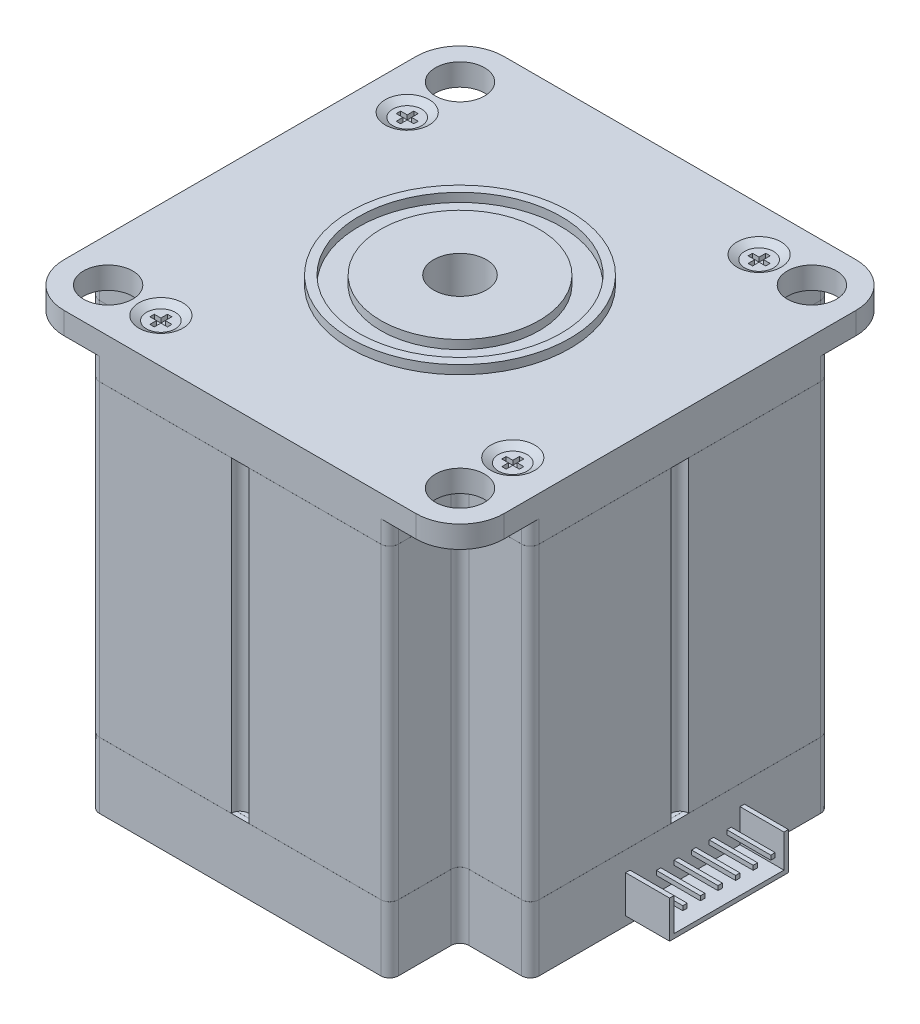
SolidWorks part; units mm, degrees
ref_plane "Front Plane" through (0, 0, 0) normal (0, 0, 1) x (1, 0, 0)
ref_plane "Top Plane" through (0, 0, 0) normal (0, 1, 0) x (1, 0, 0)
ref_plane "Right Plane" through (0, 0, 0) normal (1, 0, 0) x (0, 0, -1)
sketch "Sketch1" plane through (0, 0, 0) normal (0, 1, 0) x (1, 0, 0)
  line L1 (-40, 50) -> (40, 50)
  line L2 (-50, 40) -> (-50, -40)
  line L3 (-40, -50) -> (40, -50)
  line L4 (50, 40) -> (50, -40)
  line L5 (-50, 50) -> (50, -50) construction
  line L6 (-50, -50) -> (50, 50) construction
  arc A0 (40, -50) -> (50, -40) centre (40, -40) ccw
  arc A1 (-40, -50) -> (-50, -40) centre (-40, -40) cw
  arc A2 (40, 50) -> (50, 40) centre (40, 40) cw
  arc A3 (-40, 50) -> (-50, 40) centre (-40, 40) ccw
  circle A4 centre (-40, 40) radius 5.5806
  circle A5 centre (-40, -40) radius 5.5806
  circle A6 centre (40, -40) radius 5.5806
  circle A7 centre (40, 40) radius 5.5806
  point P0 (0, 0)
  dimension "D3" = 10
  dimension "D1" = 100
  dimension "D2" = 100
extrude "Boss-Extrude1" add sketch "Sketch1" along normal mid plane 5
sketch "Sketch2" plane through (0, 2.5, 0) normal (0, 1, 0) x (1, 0, 0)
  line L0 (50, -40) -> (50, 40) construction
  line L1 (-40, -50) -> (40, -50) construction
  line L2 (-50, 40) -> (-50, -40) construction
  line L3 (40, 50) -> (-40, 50) construction
  circle A0 centre (-40, 28) radius 5
  circle A1 centre (28, 40) radius 5
  circle A2 centre (-28, -40) radius 5
  circle A3 centre (40, -28) radius 5
  circle A4 centre (40, 40) radius 5.5806 construction
  circle A5 centre (-40, 40) radius 5.5806 construction
  circle A6 centre (-40, -40) radius 5.5806 construction
  circle A7 centre (40, -40) radius 5.5806 construction
  dimension "D1" = 12
  dimension "D3" = 12
  dimension "D4" = 12
  dimension "D5" = 10
  dimension "D6" = 10
  dimension "D7" = 10
  dimension "D8" = 10
  dimension "D9" = 10
  dimension "D2" = 12
extrude "Cut-Extrude1" cut sketch "Sketch2" against normal blind 1 draft 60
sketch "Sketch3" plane through (0, 1.5, 0) normal (0, 1, 0) x (1, 0, 0)
  line L0 (-39.5, 28.5) -> (-38, 28.5)
  line L1 (-42, 28.5) -> (-40.5, 28.5)
  line L2 (-42, 28.5) -> (-42, 27.5)
  line L3 (-42, 27.5) -> (-40.5, 27.5)
  line L4 (-38, 28.5) -> (-38, 27.5)
  line L5 (27.5, 39.5) -> (27.5, 38)
  line L6 (26, 40.5) -> (27.5, 40.5)
  line L7 (-40.5, 30) -> (-39.5, 30)
  line L8 (-40.5, 30) -> (-40.5, 28.5)
  line L9 (-40.5, 26) -> (-39.5, 26)
  line L10 (-39.5, 30) -> (-39.5, 28.5)
  line L11 (26, 40.5) -> (26, 39.5)
  line L12 (-39.5, 27.5) -> (-39.5, 26)
  line L13 (-40.5, 27.5) -> (-40.5, 26)
  line L14 (-39.5, 27.5) -> (-38, 27.5)
  line L15 (26, 39.5) -> (27.5, 39.5)
  line L16 (30, 40.5) -> (30, 39.5)
  line L17 (-27.5, -40.5) -> (-27.5, -42)
  line L18 (40.5, -27.5) -> (42, -27.5)
  line L19 (27.5, 42) -> (28.5, 42)
  line L20 (27.5, 42) -> (27.5, 40.5)
  line L21 (27.5, 38) -> (28.5, 38)
  line L22 (28.5, 42) -> (28.5, 40.5)
  line L23 (28.5, 39.5) -> (30, 39.5)
  line L24 (28.5, 39.5) -> (28.5, 38)
  line L25 (38, -27.5) -> (39.5, -27.5)
  line L26 (38, -27.5) -> (38, -28.5)
  line L27 (38, -28.5) -> (39.5, -28.5)
  line L28 (42, -27.5) -> (42, -28.5)
  line L31 (39.5, -26) -> (40.5, -26)
  line L32 (39.5, -26) -> (39.5, -27.5)
  line L33 (39.5, -30) -> (40.5, -30)
  line L34 (40.5, -26) -> (40.5, -27.5)
  line L37 (-30, -39.5) -> (-28.5, -39.5)
  line L38 (-30, -39.5) -> (-30, -40.5)
  line L39 (-30, -40.5) -> (-28.5, -40.5)
  line L40 (-26, -39.5) -> (-26, -40.5)
  line L41 (-27.5, -39.5) -> (-26, -39.5)
  line L42 (39.5, -28.5) -> (39.5, -30)
  line L43 (-28.5, -38) -> (-27.5, -38)
  line L44 (-28.5, -38) -> (-28.5, -39.5)
  line L45 (-28.5, -42) -> (-27.5, -42)
  line L46 (-27.5, -38) -> (-27.5, -39.5)
  line L47 (40.5, -28.5) -> (40.5, -30)
  line L48 (-28.5, -40.5) -> (-28.5, -42)
  line L49 (40.5, -28.5) -> (42, -28.5)
  line L50 (28.5, 40.5) -> (30, 40.5)
  line L53 (-27.5, -40.5) -> (-26, -40.5)
  point P0 (-40, 28)
  point P6 (-40, 28)
  point P12 (28, 40)
  point P21 (28, 40)
  point P26 (40, -28)
  point P32 (40, -28)
  point P37 (-28, -40)
  point P43 (-28, -40)
  dimension "D1" = 4
  dimension "D2" = 1
  dimension "D3" = 1
  dimension "D4" = 4
  dimension "D5" = 4
  dimension "D6" = 4
  dimension "D7" = 1
  dimension "D8" = 1
  dimension "D9" = 1
  dimension "D10" = 4
  dimension "D11" = 4
  dimension "D12" = 1
  dimension "D13" = 1
  dimension "D14" = 4
  dimension "D15" = 4
  dimension "D16" = 1
extrude "Cut-Extrude2" cut sketch "Sketch3" against normal blind 1
sketch "Sketch4" plane through (0, -2.5, 0) normal (0, -1, 0) x (1, 0, 0)
  line L0 (-34, 48) -> (-34, 36)
  line L1 (-40, 50) -> (40, 50) construction
  line L2 (-36, 34) -> (-48, 34)
  line L3 (-50, -40) -> (-50, 40) construction
  line L4 (-50, 32) -> (-50, -32)
  line L5 (-48, -34) -> (-36, -34)
  line L6 (-34, -36) -> (-34, -48)
  line L7 (40, -50) -> (-40, -50) construction
  line L8 (-32, -50) -> (32, -50)
  line L9 (34, -48) -> (34, -36)
  line L10 (36, -34) -> (48, -34)
  line L11 (50, 40) -> (50, -40) construction
  line L12 (50, -32) -> (50, 32)
  line L13 (48, 34) -> (36, 34)
  line L14 (34, 36) -> (34, 48)
  line L15 (32, 50) -> (-32, 50)
  arc A0 (32, 50) -> (34, 48) centre (32, 48) cw
  arc A1 (-34, 48) -> (-32, 50) centre (-32, 48) cw
  arc A2 (-32, -50) -> (-34, -48) centre (-32, -48) cw
  arc A3 (32, -50) -> (34, -48) centre (32, -48) ccw
  arc A4 (48, -34) -> (50, -32) centre (48, -32) ccw
  arc A5 (50, 32) -> (48, 34) centre (48, 32) ccw
  arc A6 (-50, 32) -> (-48, 34) centre (-48, 32) cw
  arc A7 (-50, -32) -> (-48, -34) centre (-48, -32) ccw
  arc A8 (-36, -34) -> (-34, -36) centre (-36, -36) cw
  arc A9 (34, -36) -> (36, -34) centre (36, -36) cw
  arc A10 (34, 36) -> (36, 34) centre (36, 36) ccw
  arc A11 (-34, 36) -> (-36, 34) centre (-36, 36) cw
  point P22 (34, 50)
  point P25 (-34, 50)
  point P28 (-34, -50)
  point P31 (34, -50)
  point P34 (50, -34)
  point P37 (50, 34)
  point P40 (-50, 34)
  point P43 (-50, -34)
  point P46 (-34, -34)
  point P49 (34, -34)
  point P52 (34, 34)
  point P55 (-34, 34)
  dimension "D9" = 2
  dimension "D1" = 16
  dimension "D2" = 16
  dimension "D3" = 16
  dimension "D4" = 16
  dimension "D5" = 16
  dimension "D6" = 16
  dimension "D7" = 16
  dimension "D8" = 16
extrude "Boss-Extrude2" add sketch "Sketch4" along normal blind 5
sketch "Sketch9" plane through (0, -7.5, 0) normal (0, -1, 0) x (1, 0, 0)
  line L24 (32, 49) -> (-32, 49)
  line L25 (-33, 48) -> (-33, 36)
  line L26 (-36, 33) -> (-48, 33)
  line L27 (-49, 32) -> (-49, -32)
  line L28 (-48, -33) -> (-36, -33)
  line L29 (-33, -36) -> (-33, -48)
  line L30 (-32, -49) -> (32, -49)
  line L31 (33, -48) -> (33, -36)
  line L32 (36, -33) -> (48, -33)
  line L33 (49, -32) -> (49, 32)
  line L34 (48, 33) -> (36, 33)
  line L35 (33, 36) -> (33, 48)
  line L36 (32, 49) -> (-32, 49)
  line L37 (-33, 48) -> (-33, 36)
  line L38 (-36, 33) -> (-48, 33)
  line L39 (-49, 32) -> (-49, -32)
  line L40 (-48, -33) -> (-36, -33)
  line L41 (-33, -36) -> (-33, -48)
  line L42 (-32, -49) -> (32, -49)
  line L43 (33, -48) -> (33, -36)
  line L44 (36, -33) -> (48, -33)
  line L45 (49, -32) -> (49, 32)
  line L46 (48, 33) -> (36, 33)
  line L47 (33, 36) -> (33, 48)
  arc A24 (33, 48) -> (32, 49) centre (32, 48) ccw
  arc A25 (-32, 49) -> (-33, 48) centre (-32, 48) ccw
  arc A26 (-36, 33) -> (-33, 36) centre (-36, 36) ccw
  arc A27 (-48, 33) -> (-49, 32) centre (-48, 32) ccw
  arc A28 (-49, -32) -> (-48, -33) centre (-48, -32) ccw
  arc A29 (-33, -36) -> (-36, -33) centre (-36, -36) ccw
  arc A30 (-33, -48) -> (-32, -49) centre (-32, -48) ccw
  arc A31 (32, -49) -> (33, -48) centre (32, -48) ccw
  arc A32 (36, -33) -> (33, -36) centre (36, -36) ccw
  arc A33 (48, -33) -> (49, -32) centre (48, -32) ccw
  arc A34 (49, 32) -> (48, 33) centre (48, 32) ccw
  arc A35 (33, 36) -> (36, 33) centre (36, 36) ccw
  arc A36 (33, 48) -> (32, 49) centre (32, 48) ccw
  arc A37 (-32, 49) -> (-33, 48) centre (-32, 48) ccw
  arc A38 (-36, 33) -> (-33, 36) centre (-36, 36) ccw
  arc A39 (-48, 33) -> (-49, 32) centre (-48, 32) ccw
  arc A40 (-49, -32) -> (-48, -33) centre (-48, -32) ccw
  arc A41 (-33, -36) -> (-36, -33) centre (-36, -36) ccw
  arc A42 (-33, -48) -> (-32, -49) centre (-32, -48) ccw
  arc A43 (32, -49) -> (33, -48) centre (32, -48) ccw
  arc A44 (36, -33) -> (33, -36) centre (36, -36) ccw
  arc A45 (48, -33) -> (49, -32) centre (48, -32) ccw
  arc A46 (49, 32) -> (48, 33) centre (48, 32) ccw
  arc A47 (33, 36) -> (36, 33) centre (36, 36) ccw
  dimension "D1" = 1
extrude "Boss-Extrude5" add sketch "Sketch9" along normal blind 0.01
sketch "Sketch10" plane through (0, -7.51, 0) normal (0, -1, 0) x (1, 0, 0)
  line L13 (2, -50) -> (32, -50)
  line L14 (50, 2) -> (50, 32)
  line L15 (-2, 50) -> (-32, 50)
  line L16 (-50, -2) -> (-50, -32)
  line L24 (32, 50) -> (-32, 50)
  line L25 (-34, 48) -> (-34, 36)
  line L26 (-36, 34) -> (-48, 34)
  line L27 (-50, 32) -> (-50, -32)
  line L28 (-48, -34) -> (-36, -34)
  line L29 (-34, -36) -> (-34, -48)
  line L30 (-32, -50) -> (32, -50)
  line L31 (34, -48) -> (34, -36)
  line L32 (36, -34) -> (48, -34)
  line L33 (50, -32) -> (50, 32)
  line L34 (48, 34) -> (36, 34)
  line L35 (34, 36) -> (34, 48)
  line L36 (32, 50) -> (2, 50)
  line L37 (-34, 48) -> (-34, 36)
  line L38 (-36, 34) -> (-48, 34)
  line L39 (-50, 32) -> (-50, 2)
  line L40 (-48, -34) -> (-36, -34)
  line L41 (-34, -36) -> (-34, -48)
  line L42 (-32, -50) -> (-2, -50)
  line L43 (34, -48) -> (34, -36)
  line L44 (36, -34) -> (48, -34)
  line L45 (50, -32) -> (50, -2)
  line L46 (48, 34) -> (36, 34)
  line L47 (34, 36) -> (34, 48)
  arc A12 (-50, -2) -> (-50, 2) centre (-50, 0) ccw
  arc A14 (-2, 50) -> (2, 50) centre (0, 50) ccw
  arc A15 (2, -50) -> (-2, -50) centre (0, -50) ccw
  arc A16 (50, 2) -> (50, -2) centre (50, 0) ccw
  arc A24 (34, 48) -> (32, 50) centre (32, 48) ccw
  arc A25 (-32, 50) -> (-34, 48) centre (-32, 48) ccw
  arc A26 (-36, 34) -> (-34, 36) centre (-36, 36) ccw
  arc A27 (-48, 34) -> (-50, 32) centre (-48, 32) ccw
  arc A28 (-50, -32) -> (-48, -34) centre (-48, -32) ccw
  arc A29 (-34, -36) -> (-36, -34) centre (-36, -36) ccw
  arc A30 (-34, -48) -> (-32, -50) centre (-32, -48) ccw
  arc A31 (32, -50) -> (34, -48) centre (32, -48) ccw
  arc A32 (36, -34) -> (34, -36) centre (36, -36) ccw
  arc A33 (48, -34) -> (50, -32) centre (48, -32) ccw
  arc A34 (50, 32) -> (48, 34) centre (48, 32) ccw
  arc A35 (34, 36) -> (36, 34) centre (36, 36) ccw
  arc A36 (34, 48) -> (32, 50) centre (32, 48) ccw
  arc A37 (-32, 50) -> (-34, 48) centre (-32, 48) ccw
  arc A38 (-36, 34) -> (-34, 36) centre (-36, 36) ccw
  arc A39 (-48, 34) -> (-50, 32) centre (-48, 32) ccw
  arc A40 (-50, -32) -> (-48, -34) centre (-48, -32) ccw
  arc A41 (-34, -36) -> (-36, -34) centre (-36, -36) ccw
  arc A42 (-34, -48) -> (-32, -50) centre (-32, -48) ccw
  arc A43 (32, -50) -> (34, -48) centre (32, -48) ccw
  arc A44 (36, -34) -> (34, -36) centre (36, -36) ccw
  arc A45 (48, -34) -> (50, -32) centre (48, -32) ccw
  arc A46 (50, 32) -> (48, 34) centre (48, 32) ccw
  arc A47 (34, 36) -> (36, 34) centre (36, 36) ccw
  dimension "D2" = 4
  dimension "D3" = 4
  dimension "D4" = 4
  dimension "D5" = 4
  dimension "D1" = 1
extrude "Boss-Extrude6" add sketch "Sketch10" along normal blind 70
sketch "Sketch12" plane through (0, -77.51, 0) normal (0, -1, 0) x (1, 0, 0)
  line L16 (-49, 2.8284) -> (-49, -2.8284)
  line L17 (-2.8284, 49) -> (2.8284, 49)
  line L18 (49, 2.8284) -> (49, -2.8284)
  line L19 (-2.8284, -49) -> (2.8284, -49)
  line L32 (-2.8284, 49) -> (-32, 49)
  line L33 (-33, 48) -> (-33, 36)
  line L34 (-36, 33) -> (-48, 33)
  line L35 (-49, 32) -> (-49, 2.8284)
  line L36 (-49, -2.8284) -> (-49, -32)
  line L37 (-48, -33) -> (-36, -33)
  line L38 (-33, -36) -> (-33, -48)
  line L39 (-32, -49) -> (-2.8284, -49)
  line L40 (2.8284, -49) -> (32, -49)
  line L41 (33, -48) -> (33, -36)
  line L42 (36, -33) -> (48, -33)
  line L43 (49, -32) -> (49, -2.8284)
  line L44 (49, 2.8284) -> (49, 32)
  line L45 (48, 33) -> (36, 33)
  line L46 (33, 36) -> (33, 48)
  line L47 (32, 49) -> (2.8284, 49)
  line L48 (-2.8284, 49) -> (-32, 49)
  line L49 (-33, 48) -> (-33, 36)
  line L50 (-36, 33) -> (-48, 33)
  line L51 (-49, 32) -> (-49, 2.8284)
  line L52 (-49, -2.8284) -> (-49, -32)
  line L53 (-48, -33) -> (-36, -33)
  line L54 (-33, -36) -> (-33, -48)
  line L55 (-32, -49) -> (-2.8284, -49)
  line L56 (2.8284, -49) -> (32, -49)
  line L57 (33, -48) -> (33, -36)
  line L58 (36, -33) -> (48, -33)
  line L59 (49, -32) -> (49, -2.8284)
  line L60 (49, 2.8284) -> (49, 32)
  line L61 (48, 33) -> (36, 33)
  line L62 (33, 36) -> (33, 48)
  line L63 (32, 49) -> (2.8284, 49)
  arc A32 (-2.8284, 49) -> (2.8284, 49) centre (0, 50) ccw
  arc A33 (-32, 49) -> (-33, 48) centre (-32, 48) ccw
  arc A34 (-36, 33) -> (-33, 36) centre (-36, 36) ccw
  arc A35 (-48, 33) -> (-49, 32) centre (-48, 32) ccw
  arc A36 (-49, -2.8284) -> (-49, 2.8284) centre (-50, 0) ccw
  arc A37 (-49, -32) -> (-48, -33) centre (-48, -32) ccw
  arc A38 (-33, -36) -> (-36, -33) centre (-36, -36) ccw
  arc A39 (-33, -48) -> (-32, -49) centre (-32, -48) ccw
  arc A40 (2.8284, -49) -> (-2.8284, -49) centre (0, -50) ccw
  arc A41 (32, -49) -> (33, -48) centre (32, -48) ccw
  arc A42 (36, -33) -> (33, -36) centre (36, -36) ccw
  arc A43 (48, -33) -> (49, -32) centre (48, -32) ccw
  arc A44 (49, 2.8284) -> (49, -2.8284) centre (50, 0) ccw
  arc A45 (49, 32) -> (48, 33) centre (48, 32) ccw
  arc A46 (33, 36) -> (36, 33) centre (36, 36) ccw
  arc A47 (33, 48) -> (32, 49) centre (32, 48) ccw
  arc A49 (-32, 49) -> (-33, 48) centre (-32, 48) ccw
  arc A50 (-36, 33) -> (-33, 36) centre (-36, 36) ccw
  arc A51 (-48, 33) -> (-49, 32) centre (-48, 32) ccw
  arc A53 (-49, -32) -> (-48, -33) centre (-48, -32) ccw
  arc A54 (-33, -36) -> (-36, -33) centre (-36, -36) ccw
  arc A55 (-33, -48) -> (-32, -49) centre (-32, -48) ccw
  arc A57 (32, -49) -> (33, -48) centre (32, -48) ccw
  arc A58 (36, -33) -> (33, -36) centre (36, -36) ccw
  arc A59 (48, -33) -> (49, -32) centre (48, -32) ccw
  arc A61 (49, 32) -> (48, 33) centre (48, 32) ccw
  arc A62 (33, 36) -> (36, 33) centre (36, 36) ccw
  arc A63 (33, 48) -> (32, 49) centre (32, 48) ccw
  dimension "D1" = 1
extrude "Boss-Extrude8" add sketch "Sketch12" along normal blind 0.01
sketch "Sketch13" plane through (0, -77.52, 0) normal (0, -1, 0) x (1, 0, 0)
  line L24 (32, 50) -> (-32, 50)
  line L25 (-34, 48) -> (-34, 36)
  line L26 (-36, 34) -> (-48, 34)
  line L27 (-50, 32) -> (-50, -32)
  line L28 (-48, -34) -> (-36, -34)
  line L29 (-34, -36) -> (-34, -48)
  line L30 (-32, -50) -> (32, -50)
  line L31 (34, -48) -> (34, -36)
  line L32 (36, -34) -> (48, -34)
  line L33 (50, -32) -> (50, 32)
  line L34 (48, 34) -> (36, 34)
  line L35 (34, 36) -> (34, 48)
  line L36 (32, 50) -> (-32, 50)
  line L37 (-34, 48) -> (-34, 36)
  line L38 (-36, 34) -> (-48, 34)
  line L39 (-50, 32) -> (-50, -32)
  line L40 (-48, -34) -> (-36, -34)
  line L41 (-34, -36) -> (-34, -48)
  line L42 (-32, -50) -> (32, -50)
  line L43 (34, -48) -> (34, -36)
  line L44 (36, -34) -> (48, -34)
  line L45 (50, -32) -> (50, 32)
  line L46 (48, 34) -> (36, 34)
  line L47 (34, 36) -> (34, 48)
  arc A24 (-32, 50) -> (-34, 48) centre (-32, 48) ccw
  arc A25 (-36, 34) -> (-34, 36) centre (-36, 36) ccw
  arc A26 (-48, 34) -> (-50, 32) centre (-48, 32) ccw
  arc A27 (-50, -32) -> (-48, -34) centre (-48, -32) ccw
  arc A28 (-34, -36) -> (-36, -34) centre (-36, -36) ccw
  arc A29 (-34, -48) -> (-32, -50) centre (-32, -48) ccw
  arc A30 (32, -50) -> (34, -48) centre (32, -48) ccw
  arc A31 (36, -34) -> (34, -36) centre (36, -36) ccw
  arc A32 (48, -34) -> (50, -32) centre (48, -32) ccw
  arc A33 (50, 32) -> (48, 34) centre (48, 32) ccw
  arc A34 (34, 36) -> (36, 34) centre (36, 36) ccw
  arc A35 (34, 48) -> (32, 50) centre (32, 48) ccw
  arc A36 (-32, 50) -> (-34, 48) centre (-32, 48) ccw
  arc A37 (-36, 34) -> (-34, 36) centre (-36, 36) ccw
  arc A38 (-48, 34) -> (-50, 32) centre (-48, 32) ccw
  arc A39 (-50, -32) -> (-48, -34) centre (-48, -32) ccw
  arc A40 (-34, -36) -> (-36, -34) centre (-36, -36) ccw
  arc A41 (-34, -48) -> (-32, -50) centre (-32, -48) ccw
  arc A42 (32, -50) -> (34, -48) centre (32, -48) ccw
  arc A43 (36, -34) -> (34, -36) centre (36, -36) ccw
  arc A44 (48, -34) -> (50, -32) centre (48, -32) ccw
  arc A45 (50, 32) -> (48, 34) centre (48, 32) ccw
  arc A46 (34, 36) -> (36, 34) centre (36, 36) ccw
  arc A47 (34, 48) -> (32, 50) centre (32, 48) ccw
  dimension "D1" = 1
extrude "Boss-Extrude9" add sketch "Sketch13" along normal blind 15
sketch "Sketch14" plane through (50, 0, 0) normal (1, 0, 0) x (0, 0, -1)
  line L0 (32, -92.52) -> (-32, -92.52) construction
  line L2 (13.6509, -89.52) -> (-11.3491, -89.52)
  line L3 (13.6509, -89.52) -> (13.6509, -82.02)
  line L5 (-11.3491, -89.52) -> (-11.3491, -82.02)
  line L6 (-12.3491, -90.52) -> (-12.3491, -82.02)
  line L7 (14.6509, -90.52) -> (-12.3491, -90.52)
  line L8 (14.6509, -90.52) -> (14.6509, -82.02)
  line L9 (-11.3491, -82.02) -> (-12.3491, -82.02)
  line L10 (-12.3491, -82.02) -> (-11.3491, -82.02)
  line L11 (13.6509, -82.02) -> (14.6509, -82.02)
  line L12 (13.6509, -82.02) -> (-11.3491, -82.02) construction
  line L13 (14.6509, -81.02) -> (-12.3491, -81.02) construction
  line L14 (14.6509, -90.52) -> (14.6509, -81.02) construction
  line L16 (-12.3491, -90.52) -> (-12.3491, -81.02) construction
  dimension "D1" = 3
  dimension "2.5" = 25
  dimension ".75" = 7.5
  dimension "D2" = 1
extrude "Boss-Extrude10" add sketch "Sketch14" along normal blind 10 contours L11 L3 L2 L5 L9 L6 L7 L8
sketch "Sketch15" plane through (50, 0, 0) normal (1, 0, 0) x (0, 0, -1)
  line L0 (13.6509, -89.52) -> (-11.3491, -89.52) construction
  line L1 (-9.3491, -85.02) -> (-8.3491, -85.02)
  line L2 (-9.3491, -85.02) -> (-9.3491, -86.02)
  line L3 (-9.3491, -86.02) -> (-8.3491, -86.02)
  line L4 (-8.3491, -85.02) -> (-8.3491, -86.02)
  line L5 (-9.3491, -85.02) -> (-8.3491, -86.02) construction
  line L6 (-9.3491, -86.02) -> (-8.3491, -85.02) construction
  line L7 (-5.3491, -85.065) -> (-4.3491, -85.065)
  line L8 (-5.3491, -85.065) -> (-5.3491, -86.065)
  line L9 (-5.3491, -86.065) -> (-4.3491, -86.065)
  line L10 (-4.3491, -85.065) -> (-4.3491, -86.065)
  line L11 (-1.3491, -85.065) -> (-0.3491, -85.065)
  line L12 (-1.3491, -85.065) -> (-1.3491, -86.065)
  line L13 (-1.3491, -86.065) -> (-0.3491, -86.065)
  line L14 (-0.3491, -85.065) -> (-0.3491, -86.065)
  line L15 (2.6509, -85.065) -> (3.6509, -85.065)
  line L16 (2.6509, -85.065) -> (2.6509, -86.065)
  line L17 (2.6509, -86.065) -> (3.6509, -86.065)
  line L18 (3.6509, -85.065) -> (3.6509, -86.065)
  line L19 (6.6509, -85.065) -> (7.6509, -85.065)
  line L20 (6.6509, -85.065) -> (6.6509, -86.065)
  line L21 (6.6509, -86.065) -> (7.6509, -86.065)
  line L22 (7.6509, -85.065) -> (7.6509, -86.065)
  line L23 (10.6509, -85.065) -> (11.6509, -85.065)
  line L24 (10.6509, -85.065) -> (10.6509, -86.065)
  line L25 (10.6509, -86.065) -> (11.6509, -86.065)
  line L26 (11.6509, -85.065) -> (11.6509, -86.065)
  line L27 (-11.3491, -89.52) -> (-11.3491, -82.02) construction
  point P0 (-8.8491, -85.52)
  point P25 (-4.8491, -86.065)
  point P30 (3.1509, -86.065)
  dimension "D1" = 3.5
  dimension ".2" = 2
  dimension "D3" = 1
  dimension "D4" = 1
  dimension "D5" = 3
  dimension "D6" = 3
  dimension "D7" = 3
  dimension "D8" = 3
  dimension "D9" = 3
extrude "Boss-Extrude11" add sketch "Sketch15" along normal blind 10
sketch "Sketch19" plane through (0, 2.5, 0) normal (0, 1, 0) x (1, 0, 0)
  circle A0 centre (0, 0) radius 25
  circle A1 centre (0, 0) radius 23
  circle A2 centre (0, 0) radius 18
  dimension "D1" = 2
  dimension "D2" = 5
extrude "Boss-Extrude14" add sketch "Sketch19" along normal blind 2 contours A2 | A0 A1
sketch "Sketch20" plane through (0, 4.5, 0) normal (0, 1, 0) x (1, 0, 0)
  circle A0 centre (0, 0) radius 6
  dimension "D1" = 12
extrude "Cut-Extrude4" cut sketch "Sketch20" against normal through all both and the other way through all
